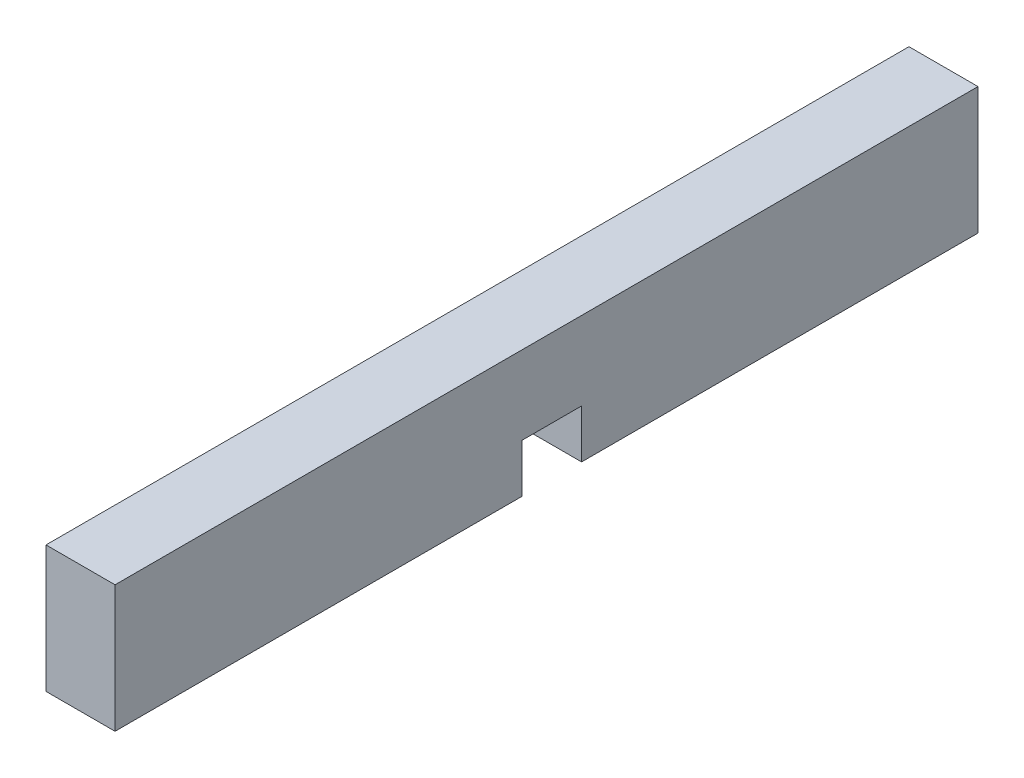
SolidWorks part; units mm, degrees
ref_plane "Front Plane" through (0, 0, 0) normal (0, 0, 1) x (1, 0, 0)
ref_plane "Top Plane" through (0, 0, 0) normal (0, 1, 0) x (1, 0, 0)
ref_plane "Right Plane" through (0, 0, 0) normal (1, 0, 0) x (0, 0, -1)
sketch "Sketch1" plane through (0, 0, 0) normal (1, 0, 0) x (0, 0, -1)
  line L1 (-29.3624, 4.318) -> (29.3624, 4.318)
  line L2 (-29.3624, 4.318) -> (-29.3624, -4.318)
  line L3 (-29.3624, -4.318) -> (29.3624, -4.318)
  line L4 (29.3624, 4.318) -> (29.3624, -4.318)
  line L5 (-29.3624, 4.318) -> (29.3624, -4.318) construction
  line L6 (-29.3624, -4.318) -> (29.3624, 4.318) construction
  point P0 (0, 0)
  dimension "D1" = 58.7248
  dimension "D2" = 8.636
extrude "Boss-Extrude1" add sketch "Sketch1" along normal mid plane 4.699
sketch "Sketch2" plane through (0, 0, 0) normal (1, 0, 0) x (0, 0, -1)
  line L0 (-29.3624, -4.318) -> (29.3624, -4.318) construction
  line L1 (-1.6764, -4.318) -> (2.3876, -4.318)
  line L2 (-1.6764, -4.318) -> (-1.6764, -1.016)
  line L3 (-1.6764, -1.016) -> (2.3876, -1.016)
  line L4 (2.3876, -4.318) -> (2.3876, -1.016)
  line L5 (-29.3624, 4.318) -> (-29.3624, -4.318) construction
  dimension "D1" = 27.686
  dimension "D2" = 4.064
  dimension "D3" = 3.302
extrude "Cut-Extrude2" cut sketch "Sketch2" against normal mid plane 116.459
